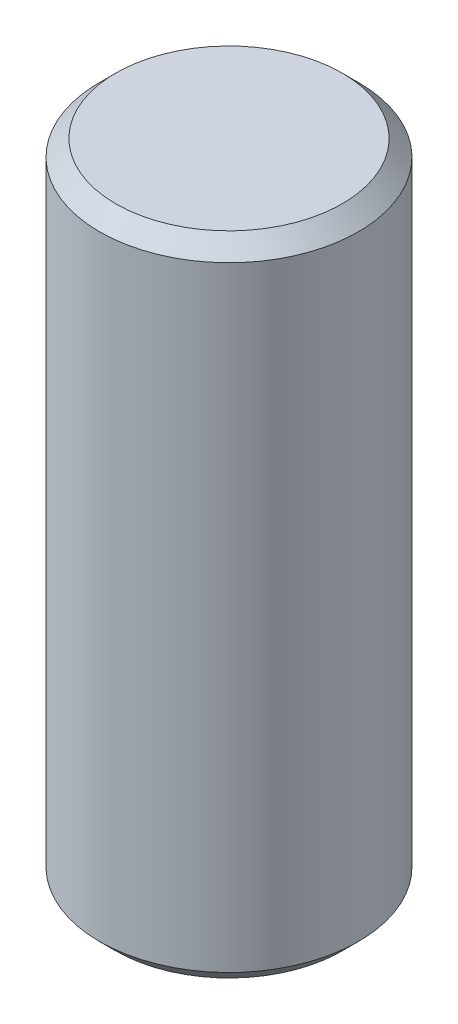
SolidWorks part; units mm, degrees
ref_plane "前视基准面" through (0, 0, 0) normal (0, 0, 1) x (1, 0, 0)
ref_plane "上视基准面" through (0, 0, 0) normal (0, 1, 0) x (1, 0, 0)
ref_plane "右视基准面" through (0, 0, 0) normal (1, 0, 0) x (0, 0, -1)
other "Configuration Table"
sketch "草图1" plane through (0, 0, 0) normal (0, 1, 0) x (1, 0, 0)
  circle A0 centre (0, 0) radius 8
  dimension "D1" = 16
extrude "凸台-拉伸1" add sketch "草图1" along normal blind 40
cosmetic thread "装饰螺纹线1" parameters "D1"=6, "D2"=13.835
chamfer "倒角1" distance 1 angle 45 2 edges at (0, 0, 8) (0, 40, 8)
